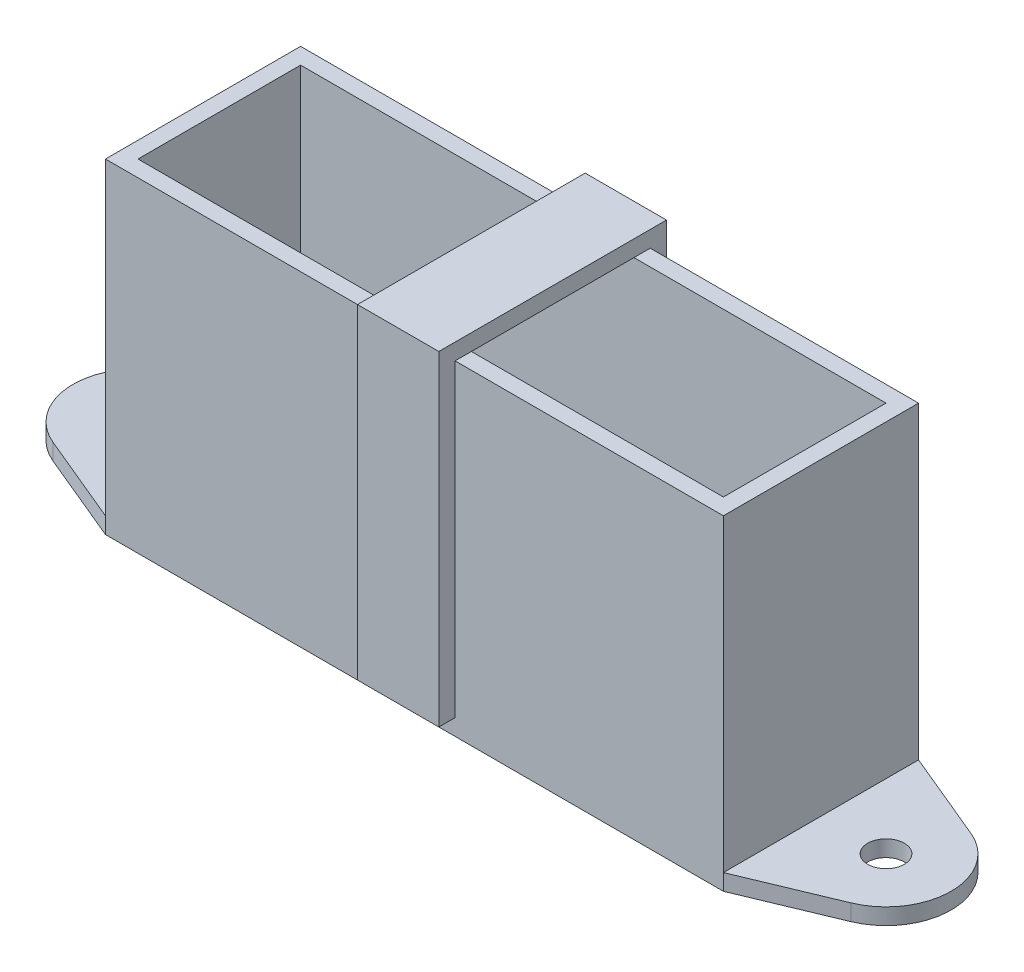
SolidWorks part; units mm, degrees
ref_plane "Front Plane" through (0, 0, 0) normal (0, 0, 1) x (1, 0, 0)
ref_plane "Top Plane" through (0, 0, 0) normal (0, 1, 0) x (1, 0, 0)
ref_plane "Right Plane" through (0, 0, 0) normal (1, 0, 0) x (0, 0, -1)
sketch "Sketch15" plane through (0, 0, 0) normal (0, 1, 0) x (1, 0, 0)
  line L0 (-38, -12) -> (-38, 12)
  line L1 (-36, -10) -> (36, -10)
  line L2 (-36, -10) -> (-36, 10)
  line L3 (-36, 10) -> (36, 10)
  line L4 (36, -10) -> (36, 10)
  line L5 (-36, -10) -> (36, 10) construction
  line L6 (-36, 10) -> (36, -10) construction
  line L7 (-38, 12) -> (38, 12)
  line L8 (38, -12) -> (38, 12)
  line L9 (-38, -12) -> (38, -12)
  point P0 (0, 0)
  dimension "D1" = 72
  dimension "D2" = 20
  dimension "D3" = 2
extrude "Boss-Extrude8" add sketch "Sketch15" along normal blind 38
sketch "Sketch16" plane through (0, 38, 0) normal (0, 1, 0) x (1, 0, 0)
  line L0 (38, 12) -> (-38, 12) construction
  line L1 (-5, 12) -> (5, 12)
  line L2 (-5, 12) -> (-5, -12)
  line L3 (-5, -12) -> (5, -12)
  line L4 (5, 12) -> (5, -12)
  line L5 (-38, -12) -> (38, -12) construction
  point P8 (0, 12)
  dimension "D1" = 10
extrude "Boss-Extrude9" add sketch "Sketch16" along normal blind 2 separate body
sketch "Sketch17" plane through (0, 0, 12) normal (0, 0, 1) x (1, 0, 0)
  line L0 (-38, 0) -> (38, 0) construction
  line L1 (-5, 40) -> (5, 40)
  line L2 (-5, 40) -> (-5, 0)
  line L3 (-5, 0) -> (5, 0)
  line L4 (5, 40) -> (5, 0)
  point P7 (5, 40)
extrude "Boss-Extrude10" add sketch "Sketch17" along normal blind 2
mirror "Mirror3" about plane through (0, 0, 0) normal (0, 0, 1) of "Boss-Extrude10"
sketch "Sketch18" plane through (0, 0, 0) normal (0, -1, 0) x (1, 0, 0)
  line L0 (-38, 12) -> (38, 12)
  line L1 (38, 12) -> (49.0769, 7.3846)
  line L2 (49.0769, -7.3846) -> (38, -12)
  line L3 (38, 12) -> (38, -12) construction
  line L4 (38, -12) -> (-38, -12)
  line L5 (-38, -12) -> (-49.0769, -7.3846)
  line L6 (-49.0769, 7.3846) -> (-38, 12)
  line L7 (-38, -12) -> (-38, 12) construction
  arc A0 (49.0769, 7.3846) -> (49.0769, -7.3846) centre (46, 0) cw
  arc A1 (-49.0769, -7.3846) -> (-49.0769, 7.3846) centre (-46, 0) cw
  dimension "D1" = 8
extrude "Boss-Extrude11" add sketch "Sketch18" along normal blind 2
hole_wizard "M4 Clearance Hole1" positions "Sketch19" profile "Sketch20" hole size "M4" standard "ANSI Metric" end condition through all
sketch "Sketch19" plane through (0, 0, 0) normal (0, 1, 0) x (1, 0, 0)
  point P0 (-46, 0)
  point P3 (46, 0)
sketch "Sketch20" plane through (-46, 0, 0) normal (1, 0, 0) x (0, 0, 1)
  line L0 (0, 0) -> (0, 2)
  line L1 (0, 2) -> (2.25, 2)
  line L2 (2.25, 2) -> (2.25, 0)
  line L5 (2.25, 0) -> (0, 0)
  line L11 (0, -6.35) -> (0, 107.95) construction
  dimension "Thru Hole Dia." = 4.5
  dimension "Thru Hole Depth" = 2
